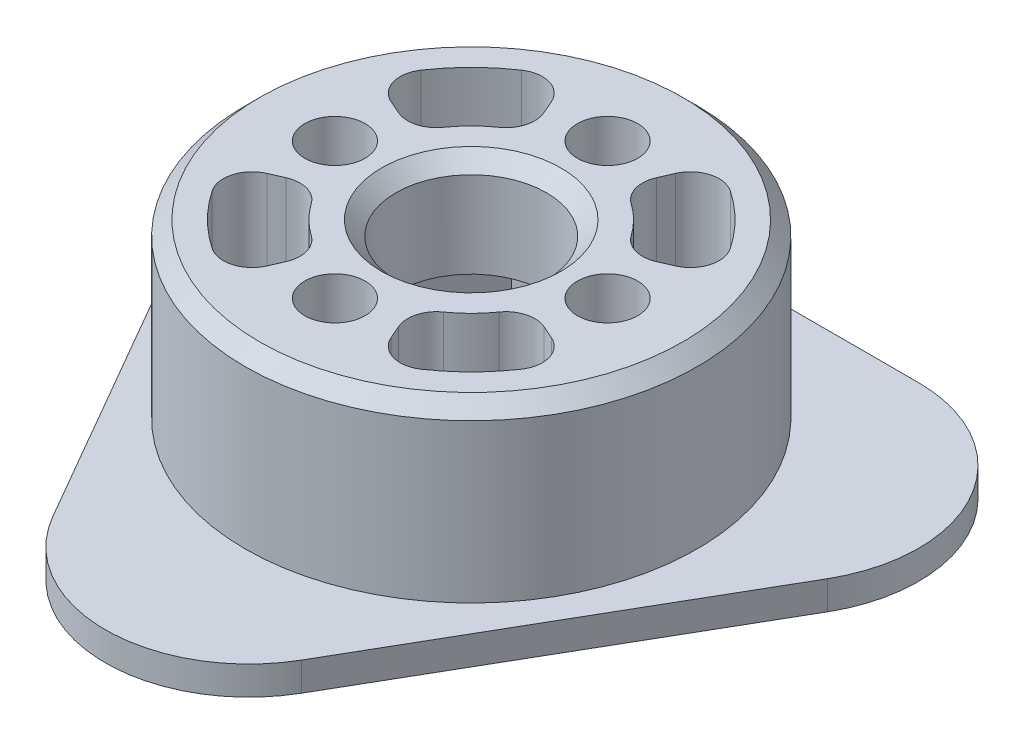
SolidWorks part; units mm, degrees
ref_plane "Спереди" through (0, 0, 0) normal (0, 0, 1) x (1, 0, 0)
ref_plane "Сверху" through (0, 0, 0) normal (0, 1, 0) x (1, 0, 0)
ref_plane "Справа" through (0, 0, 0) normal (1, 0, 0) x (0, 0, -1)
sketch "Эскиз1" plane through (0, 0, 0) normal (0, 1, 0) x (1, 0, 0)
  circle A0 centre (0, 0) radius 15.75
  circle A1 centre (0, 0) radius 5.25
  dimension "D1" = 31.5
  dimension "D2" = 10.5
extrude "Бобышка-Вытянуть1" add sketch "Эскиз1" along normal blind 12
sketch "Эскиз2" plane through (0, 0, 0) normal (0, -1, 0) x (1, 0, 0)
  line L1 (-8.6603, 20.5) -> (-22.0836, -2.75)
  line L2 (-13.4234, -17.75) -> (13.4234, -17.75)
  line L3 (22.0836, -2.75) -> (8.6603, 20.5)
  circle A0 centre (0, 0) radius 17.75 construction
  circle A1 centre (0, 0) radius 15.75 construction
  arc A2 (-22.0836, -2.75) -> (-13.4234, -17.75) centre (-13.4234, -7.75) ccw
  arc A3 (13.4234, -17.75) -> (22.0836, -2.75) centre (13.4234, -7.75) ccw
  arc A4 (8.6603, 20.5) -> (-8.6603, 20.5) centre (0, 15.5) ccw
  circle A5 centre (0, 0) radius 5.25
  circle A6 centre (0, 0) radius 5.25 construction
  dimension "D1" = 2
  dimension "D2" = 10
extrude "Бобышка-Вытянуть2" add sketch "Эскиз2" along normal blind 2
sketch "Эскиз3" plane through (0, -2, 0) normal (0, -1, 0) x (1, 0, 0)
  line L1 (3.8105, 6.6) -> (-3.8105, 6.6)
  line L2 (-3.8105, 6.6) -> (-7.621, 0)
  line L3 (-7.621, 0) -> (-3.8105, -6.6)
  line L4 (-3.8105, -6.6) -> (3.8105, -6.6)
  line L5 (3.8105, -6.6) -> (7.621, 0)
  line L6 (7.621, 0) -> (3.8105, 6.6)
  circle A0 centre (0, 0) radius 6.6 construction
  dimension "D1" = 13.2
extrude "Вырез-Вытянуть1" cut sketch "Эскиз3" against normal blind 7
sketch "Эскиз5" plane through (0, 12, 0) normal (0, 1, 0) x (1, 0, 0)
  circle A0 centre (0, 0) radius 9.5 construction
  circle A1 centre (0, 9.5) radius 1.1
  circle A2 centre (9.5, 0) radius 1.1
  circle A3 centre (0, -9.5) radius 1.1
  circle A4 centre (-9.5, 0) radius 1.1
  dimension "D1" = 19
  dimension "D2" = 2.2
  dimension "D3" = 4
extrude "Вырез-Вытянуть2" cut sketch "Эскиз5" against normal through all
sketch "Эскиз6" plane through (0, 12, 0) normal (0, 1, 0) x (1, 0, 0)
  circle A0 centre (0, 9.5) radius 2.1
  circle A1 centre (9.5, 0) radius 2.1
  circle A2 centre (0, -9.5) radius 2.1
  circle A3 centre (-9.5, 0) radius 2.1
  circle A4 centre (9.5, 0) radius 1.1 construction
  circle A5 centre (0, -9.5) radius 1.1 construction
  dimension "D2" = 4.2
  dimension "D1" = 4
extrude "Вырез-Вытянуть3" cut sketch "Эскиз6" against normal offset from surface (5 mm away) 9 up to face at (0, -2, -8.4)
chamfer "Фаска1" distance 1 angle 45 2 edges at (0, 12, 5.25) (0, 12, 15.75)
sketch "Эскиз7" plane through (0, 12, 0) normal (0, 1, 0) x (1, 0, 0)
  line L0 (0, 0) -> (0, 14.75) construction
  line L2 (10.4298, 10.4298) -> (0, 0) construction
  line L3 (0, 0) -> (5.9, 13.5186)
  line L5 (13.5186, 5.9) -> (0, 0)
  line L6 (0, 0) -> (13.5186, -5.9)
  line L7 (5.9, -13.5186) -> (0, 0)
  line L8 (0, 0) -> (-5.9, -13.5186)
  line L9 (-13.5186, -5.9) -> (0, 0)
  line L10 (0, 0) -> (-13.5186, 5.9)
  line L11 (-5.9, 13.5186) -> (0, 0)
  circle A0 centre (0, 0) radius 14.75 construction
  circle A1 centre (9.5, 0) radius 1.1 construction
  circle A2 centre (0, 0) radius 8
  circle A3 centre (0, 0) radius 13
  dimension "D3" = 16
  dimension "D4" = 26
  dimension "D1" = 3.8
  dimension "D2" = 45
  dimension "D5" = 4
extrude "Вырез-Вытянуть4" cut sketch "Эскиз7" against normal through all contours L5 A3 L3 A2 | L7 A3 L6 A2 | L9 A3 L8 A2 | L11 A3 L10 A2
fillet "Скругление1" radius 2 16 edges at (7.3321, 5, -3.2) (11.9147, 5, -5.2) (5.2, 5, -11.9147) (3.2, 5, -7.3321) (-3.2, 5, -7.3321) (-5.2, 5, -11.9147) (-11.9147, 5, -5.2) (-11.9147, 5, 5.2) (-7.3321, 5, 3.2) (-5.2, 5, 11.9147) (-3.2, 5, 7.3321) (3.2, 5, 7.3321) (5.2, 5, 11.9147) (11.9147, 5, 5.2) (7.3321, 5, 3.2) (-7.3321, 5, -3.2)
equation "\"sensor_d\" = 55"
equation "\"sensor_thikness\"= 2"
equation "\"screw_d\"= 2"
equation "\"screw_h1\"= 12"
equation "\"screw_h2\"= 8"
equation "\"screw_hh_d\"= 3.8"
equation "\"screw_hh_h\"= 2"
equation "\"print_offset\"= 0.2"
equation "\"nut_d\"= 3.8"
equation "\"nut_h\"= 2"
equation "\"mounting_r\"= \"sensor_d\" - 8"
equation "\"board_size_a\"= 37.2"
equation "\"board_size_b\"= 30.1"
equation "\"mount_hole_a\"= 12.7"
equation "\"mount_hole_b\"= 17.78"
equation "\"board_size_c\"= 20.23"
equation "\"board_size_d\"= 0.25"
equation "\"D1@Эскиз1\"=31.7-\"print_offset\""
equation "\"D2@Эскиз1\"=\"print_offset\"+10.3"
equation "\"D1@Эскиз3\"=\"print_offset\"+13"
equation "\"D2@Эскиз5\"=\"screw_d\"+\"print_offset\""
equation "\"D2@Эскиз6\"=\"screw_hh_d\"+2*\"print_offset\""
equation "\"D1@Вырез-Вытянуть3\"=12-3"
equation "\"D1@Эскиз7\"=\"screw_hh_d\""
